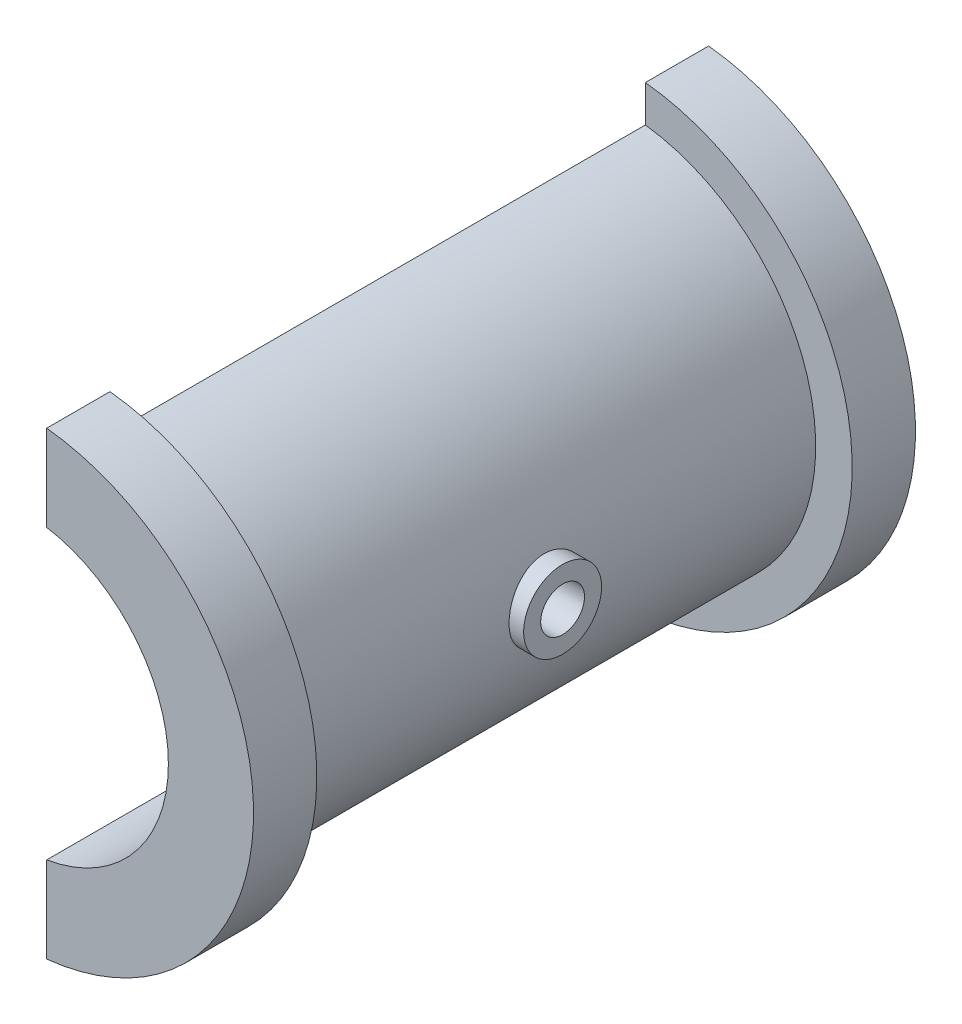
SolidWorks part; units mm, degrees
ref_plane "Front Plane" through (0, 0, 0) normal (0, 0, 1) x (1, 0, 0)
ref_plane "Top Plane" through (0, 0, 0) normal (0, 1, 0) x (1, 0, 0)
ref_plane "Right Plane" through (0, 0, 0) normal (1, 0, 0) x (0, 0, -1)
sketch "Sketch1" plane through (0, 0, 0) normal (0, 0, 1) x (1, 0, 0)
  line L0 (5, 39.6863) -> (5, 29.5804)
  line L1 (5, -29.5804) -> (5, -39.6863)
  arc A0 (5, 39.6863) -> (5, -39.6863) centre (0, 0) cw
  arc A1 (5, 29.5804) -> (5, -29.5804) centre (0, 0) cw
  dimension "D1" = 40
  dimension "D2" = 30
  dimension "D3" = 5
extrude "Boss-Extrude1" add sketch "Sketch1" along normal mid plane 110
sketch "Sketch2" plane through (0, 0, 55) normal (0, 0, 1) x (1, 0, 0)
  line L0 (5, 29.5804) -> (5, 47.2361)
  line L1 (5, -29.5804) -> (5, -47.2361)
  arc A0 (5, -29.5804) -> (5, 29.5804) centre (0, 0) ccw construction
  arc A1 (5, -29.5804) -> (5, 29.5804) centre (0, 0) ccw
  arc A2 (5, 47.2361) -> (5, -47.2361) centre (0, 0) cw
  dimension "D1" = 47.5
extrude "Boss-Extrude2" add sketch "Sketch2" along normal blind 13
mirror "Mirror1" about plane through (0, 0, 0) normal (0, 0, 1) of "Boss-Extrude2"
ref_plane "Plane1" through (43, 0, 0) normal (1, 0, 0) x (0, 0, -1)
sketch "Sketch3" plane through (43, 0, 0) normal (1, 0, 0) x (0, 0, -1)
  circle A0 centre (0, 0) radius 8
  dimension "D1" = 16
extrude "Boss-Extrude3" add sketch "Sketch3" against normal up to next
hole_wizard "Hole1" positions "Sketch4" profile "Sketch5" legacy end condition through all
sketch "Sketch4" plane through (43, 0, 0) normal (1, 0, 0) x (0, 0, -1)
  point P0 (0, 0)
sketch "Sketch5" plane through (43, 0, 0) normal (0, 1, 0) x (0, 0, -1)
  line L0 (0, 0) -> (0, 38)
  line L1 (0, 38) -> (4.5, 38)
  line L2 (4.5, 38) -> (4.5, 0)
  line L3 (4.5, 0) -> (0, 0)
  line L4 (0, 110) -> (0, -10) construction
  dimension "Diameter" = 9
  dimension "Depth" = 38
